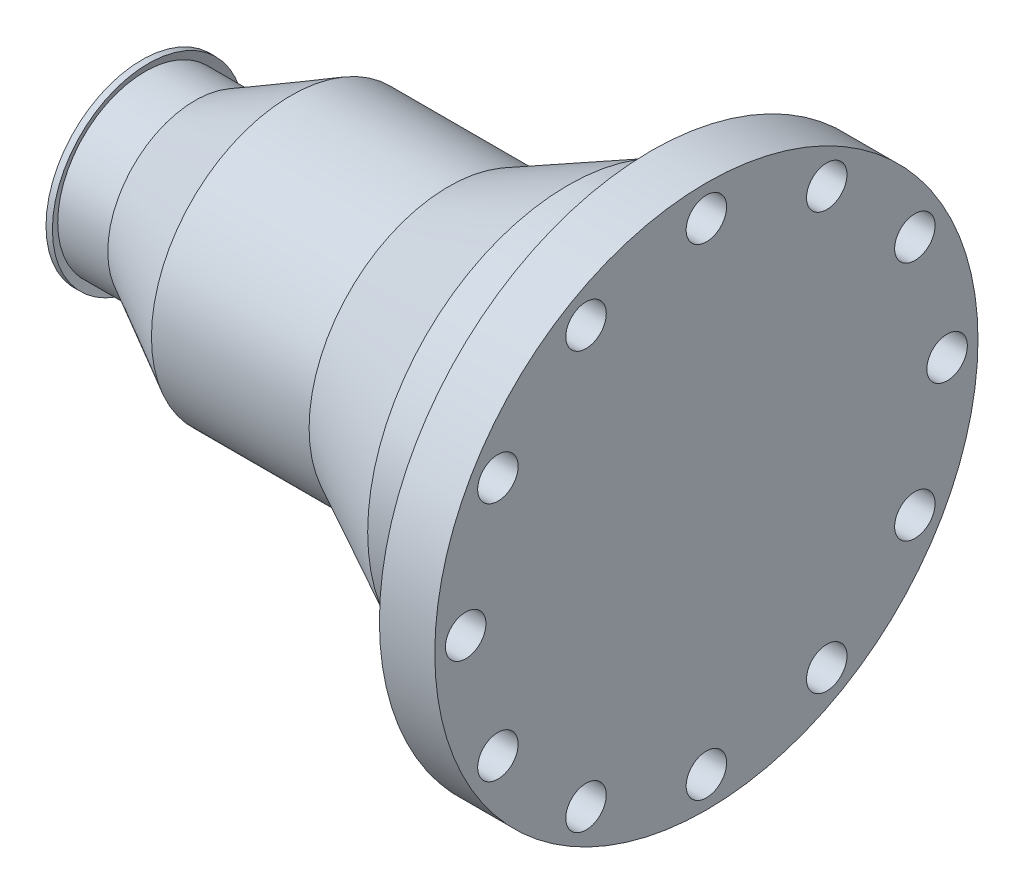
SolidWorks part; units mm, degrees
ref_plane "Спереди" through (0, 0, 0) normal (0, 0, 1) x (1, 0, 0)
ref_plane "Сверху" through (0, 0, 0) normal (0, 1, 0) x (1, 0, 0)
ref_plane "Справа" through (0, 0, 0) normal (1, 0, 0) x (0, 0, -1)
sketch "Эскиз1" plane through (0, 0, 0) normal (0, 0, 1) x (1, 0, 0)
  line L0 (0, 0) -> (265, 0)
  line L1 (0, 0) -> (0, 45)
  line L2 (0, 45) -> (3, 45)
  line L3 (3, 45) -> (1.5, 41)
  line L4 (1.5, 41) -> (25, 41)
  line L5 (25, 41) -> (70, 65.5)
  line L6 (70, 65.5) -> (144, 65.5)
  line L7 (144, 65.5) -> (200, 94)
  line L8 (200, 94) -> (220, 94)
  line L9 (220, 94) -> (220, 95)
  line L10 (220, 95) -> (239, 95)
  line L11 (239, 95) -> (239, 100)
  line L12 (239, 100) -> (239, 127.5)
  line L13 (239, 127.5) -> (265, 127.5)
  line L14 (265, 127.5) -> (265, 0)
revolve "Повернуть1" add sketch "Эскиз1" angle 360 about L0
sketch "Эскиз2" plane through (0, 0, 0) normal (0, 0, 1) x (1, 0, 0)
  line L0 (0, 0) -> (38, 0)
  line L1 (0, 0) -> (0, 31)
  line L2 (0, 45) -> (0, -45) construction
  line L3 (0, 31) -> (38, 31)
  line L4 (38, 31) -> (38, 0)
revolve "Вырез-Повернуть1" cut sketch "Эскиз2" angle 360 about L0
sketch "Эскиз3" plane through (0, 0, 0) normal (1, 0, 0) x (0, 0, -1)
  circle A0 centre (0, 113) radius 9.5
extrude "Вырез-Вытянуть1" cut sketch "Эскиз3" along normal through all
sketch "Эскиз4" plane through (0, 0, 0) normal (1, 0, 0) x (0, 0, -1)
  circle A0 centre (-56.5, 97.8609) radius 9.5
extrude "Вырез-Вытянуть2" cut sketch "Эскиз4" along normal through all
sketch "Эскиз5" plane through (0, 0, 0) normal (1, 0, 0) x (0, 0, -1)
  circle A0 centre (-97.8609, 56.5) radius 9.5
extrude "Вырез-Вытянуть3" cut sketch "Эскиз5" along normal through all
sketch "Эскиз6" plane through (0, 0, 0) normal (1, 0, 0) x (0, 0, -1)
  circle A0 centre (-113, 0) radius 9.5
extrude "Вырез-Вытянуть4" cut sketch "Эскиз6" along normal through all
sketch "Эскиз7" plane through (0, 0, 0) normal (1, 0, 0) x (0, 0, -1)
  circle A0 centre (-97.8609, -56.5) radius 9.5
extrude "Вырез-Вытянуть5" cut sketch "Эскиз7" along normal through all
sketch "Эскиз8" plane through (0, 0, 0) normal (1, 0, 0) x (0, 0, -1)
  circle A0 centre (-56.5, -97.8609) radius 9.5
extrude "Вырез-Вытянуть6" cut sketch "Эскиз8" along normal through all
sketch "Эскиз9" plane through (0, 0, 0) normal (1, 0, 0) x (0, 0, -1)
  circle A0 centre (0, -113) radius 9.5
extrude "Вырез-Вытянуть7" cut sketch "Эскиз9" along normal through all
sketch "Эскиз10" plane through (0, 0, 0) normal (1, 0, 0) x (0, 0, -1)
  circle A0 centre (56.5, -97.8609) radius 9.5
extrude "Вырез-Вытянуть8" cut sketch "Эскиз10" along normal through all
sketch "Эскиз11" plane through (0, 0, 0) normal (1, 0, 0) x (0, 0, -1)
  circle A0 centre (97.8609, -56.5) radius 9.5
extrude "Вырез-Вытянуть9" cut sketch "Эскиз11" along normal through all
sketch "Эскиз12" plane through (0, 0, 0) normal (1, 0, 0) x (0, 0, -1)
  circle A0 centre (113, 0) radius 9.5
extrude "Вырез-Вытянуть10" cut sketch "Эскиз12" along normal through all
sketch "Эскиз13" plane through (0, 0, 0) normal (1, 0, 0) x (0, 0, -1)
  circle A0 centre (97.8609, 56.5) radius 9.5
extrude "Вырез-Вытянуть11" cut sketch "Эскиз13" along normal through all
sketch "Эскиз14" plane through (0, 0, 0) normal (1, 0, 0) x (0, 0, -1)
  circle A0 centre (56.5, 97.8609) radius 9.5
extrude "Вырез-Вытянуть12" cut sketch "Эскиз14" along normal through all
